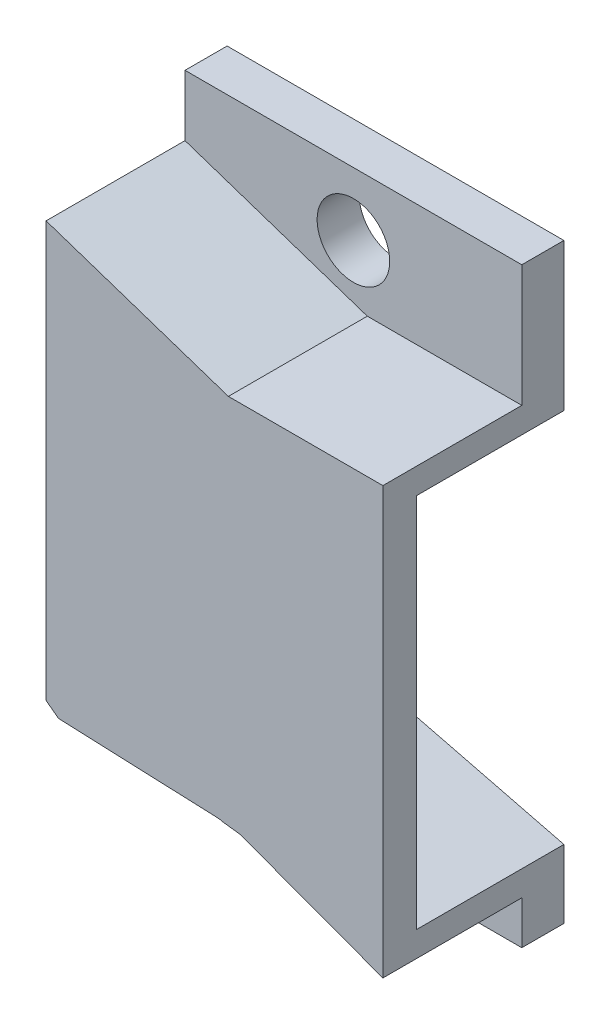
SolidWorks part; units mm, degrees
ref_plane "Plan de face" through (0, 0, 0) normal (0, 0, 1) x (1, 0, 0)
ref_plane "Plan de dessus" through (0, 0, 0) normal (0, 1, 0) x (1, 0, 0)
ref_plane "Plan de droite" through (0, 0, 0) normal (1, 0, 0) x (0, 0, -1)
sketch "Esquisse1" plane through (0, 0, 0) normal (0, 0, 1) x (1, 0, 0)
  line L1 (-13.4455, 13.9553) -> (2.5545, 13.9553)
  line L2 (-13.4455, 13.9553) -> (-13.4455, -14.1447)
  line L3 (-13.4455, -14.1447) -> (2.5545, -14.1447)
  line L4 (2.5545, 13.9553) -> (2.5545, -14.1447)
  circle A0 centre (-5.4455, 10.9553) radius 1.725
  circle A1 centre (-5.4455, -11.1447) radius 1.725
  dimension "D1" = 3.45
  dimension "D2" = 22.1
  dimension "D3" = 3
  dimension "D4" = 3
  dimension "D5" = 8
  dimension "D6" = 8
  dimension "D7" = 8
  dimension "D8" = 3
extrude "Boss.-Extru.1" add sketch "Esquisse1" along normal blind 8.6
sketch "Esquisse2" plane through (0, 0, 0) normal (0, 0, -1) x (-1, 0, 0)
  line L0 (-2.5545, -14.1447) -> (-2.5545, 13.9553) construction
  line L1 (-2.5545, 6.9553) -> (13.4455, 6.9553)
  line L2 (-2.5545, 6.9553) -> (-2.5545, -7.6447)
  line L3 (-2.5545, -7.6447) -> (13.4455, -7.6447)
  line L4 (13.4455, 6.9553) -> (13.4455, -7.6447)
  line L5 (13.4455, 13.9553) -> (13.4455, -14.1447) construction
  circle A0 centre (5.4455, 10.9553) radius 1.725 construction
  circle A1 centre (5.4455, -11.1447) radius 1.725 construction
  dimension "D1" = 4
  dimension "D2" = 3.5
extrude "Enlèv. mat.-Extru.2" cut sketch "Esquisse2" against normal blind 7
sketch "Esquisse4" plane through (0, 0, 0) normal (0, 0, -1) x (-1, 0, 0)
  line L0 (8.1033, -14.1447) -> (13.4455, -14.1447)
  line L1 (13.4455, -14.1447) -> (-2.5545, -14.1447) construction
  line L2 (13.4455, -14.1447) -> (13.4455, -8.6734)
  line L3 (13.4455, -7.6447) -> (13.4455, -14.1447) construction
  line L4 (13.4455, -8.6734) -> (6.156, -14.1447)
  line L5 (6.156, -14.1447) -> (8.1033, -14.1447)
  point P5 (13.4455, -9.3576)
  point P10 (13.4455, -8.6734)
  point P11 (6.156, -14.1447)
extrude "Enlèv. mat.-Extru.5" cut sketch "Esquisse4" against normal blind 16
sketch "Esquisse5" plane through (0, 0, 0) normal (0, 0, -1) x (-1, 0, 0)
  line L0 (-2.5545, -7.6447) -> (-2.5545, -10.8947)
  line L1 (-2.5545, -14.1447) -> (-2.5545, -7.6447) construction
  line L2 (-2.5545, -10.8947) -> (10.4455, -7.6447)
  line L3 (-2.5545, -7.6447) -> (13.4455, -7.6447) construction
  line L4 (10.4455, -7.6447) -> (-2.5545, -7.6447)
  line L5 (13.4455, 6.9553) -> (13.4455, 9.9107)
  line L6 (13.4455, 13.9553) -> (13.4455, 6.9553) construction
  line L7 (13.4455, 9.9107) -> (3.8084, 6.9553)
  line L8 (13.4455, 6.9553) -> (-2.5545, 6.9553) construction
  line L9 (3.8084, 6.9553) -> (13.4455, 6.9553)
  dimension "D1" = 13
extrude "Enlèv. mat.-Extru.6" cut sketch "Esquisse5" against normal blind 7
sketch "Esquisse6" plane through (0, 0, 0) normal (0, 0, -1) x (-1, 0, 0)
  line L2 (13.4455, -8.6734) -> (6.156, -14.1447) construction
  line L3 (12.8545, -9.117) -> (6.156, -14.1447)
  line L4 (6.156, -14.1447) -> (-2.5545, -14.1447)
  line L9 (-2.5545, 6.9553) -> (-2.5545, 13.9553) construction
  line L10 (-2.5545, 8.1694) -> (-2.5545, 13.9553)
  line L11 (-2.5545, 13.9553) -> (13.4455, 13.9553)
  line L12 (13.4455, 13.9553) -> (13.4455, 9.9107)
  line L13 (-2.5545, 8.1694) -> (4.7854, 8.1694)
  line L14 (4.7854, 8.1694) -> (13.4455, 11.0624)
  line L15 (13.4455, 11.0624) -> (13.4455, 13.9553)
  line L16 (12.8545, -9.117) -> (5.4455, -9.4197)
  line L17 (5.4455, -9.4197) -> (4.2338, -9.5714)
  line L18 (4.2338, -9.5714) -> (-2.5545, -12.0898)
  line L19 (-2.5545, -14.1447) -> (-2.5545, -10.8947) construction
  line L20 (-2.5545, -12.0898) -> (-2.5545, -14.1447)
  circle A0 centre (5.4455, -11.1447) radius 1.725 construction
  line M8 (-2.5545, -10.8947) -> (-2.5545, -14.1447)
  line M9 (-2.5545, -14.1447) -> (6.156, -14.1447)
  line M10 (6.156, -14.1447) -> (13.4455, -8.6734)
  circle M12 centre (5.4455, -11.1447) radius 1.725
extrude "Enlèv. mat.-Extru.9" cut sketch "Esquisse6" against normal blind 18 from offset 2 contours L13 L14 L12 L11 L10 | L17 L18 L16 M8 M9 M10 M12
